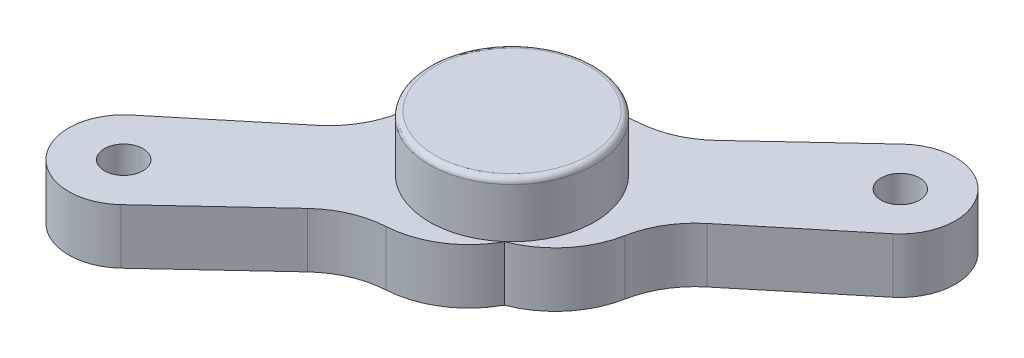
SolidWorks part; units mm, degrees
material "1060 Alloy"
ref_plane "Front Plane" through (0, 0, 0) normal (0, 0, 1) x (1, 0, 0)
ref_plane "Top Plane" through (0, 0, 0) normal (0, 1, 0) x (1, 0, 0)
ref_plane "Right Plane" through (0, 0, 0) normal (1, 0, 0) x (0, 0, -1)
sketch "Sketch1" plane through (0, 0, 0) normal (0, 1, 0) x (1, 0, 0)
  circle A0 centre (0, 0) radius 7.5
  dimension "D1" = 15
extrude "Boss-Extrude1" add sketch "Sketch1" along normal blind 5
sketch "Sketch2" plane through (0, 0, 0) normal (0, 1, 0) x (1, 0, 0)
  line L2 (0, 0) -> (37.7862, 33.1516) construction
  line L5 (12.7163, 4.995) -> (21.9739, 12.6302)
  line L6 (6.6071, 11.9583) -> (15.3819, 20.1438)
  line L7 (0, 0) -> (4.9463, -5.6378)
  line L8 (0, 0) -> (-4.9463, 5.6378)
  arc A1 (15.3819, 20.1438) -> (21.9739, 12.6302) centre (18.7925, 16.4876) cw
  arc A2 (9.9496, 0.3296) -> (4.9463, -5.6378) centre (2.0926, 1.836) cw
  arc A3 (9.9496, 0.3296) -> (12.7163, 4.995) centre (17.8065, -1.1767) cw
  circle A4 centre (18.7925, 16.4876) radius 1.75
  circle A5 centre (0, 0) radius 7.5 construction
  arc A6 (1.6214, 9.8221) -> (6.6071, 11.9583) centre (1.1501, 17.8082) ccw
  arc A7 (1.6214, 9.8221) -> (-4.9463, 5.6378) centre (2.0926, 1.836) ccw
  point P9 (0, 0)
  point P13 (0, 0)
  dimension "D4" = 8
  dimension "D6" = 5
  dimension "D2" = 3.5
  dimension "D3" = 25
  dimension "D5" = 8
  dimension "D7" = 12
  dimension "D8" = 50.2676
  dimension "D1" = 7.5
extrude "Boss-Extrude2" add sketch "Sketch2" against normal blind 5
pattern_circular "CirPattern3" count 2 over 360 about axis through (0, 0, 0) along (0, 1, 0) of "Boss-Extrude2"
fillet "Fillet5" radius 0.5 1 edges at (0, 5, 7.5)
